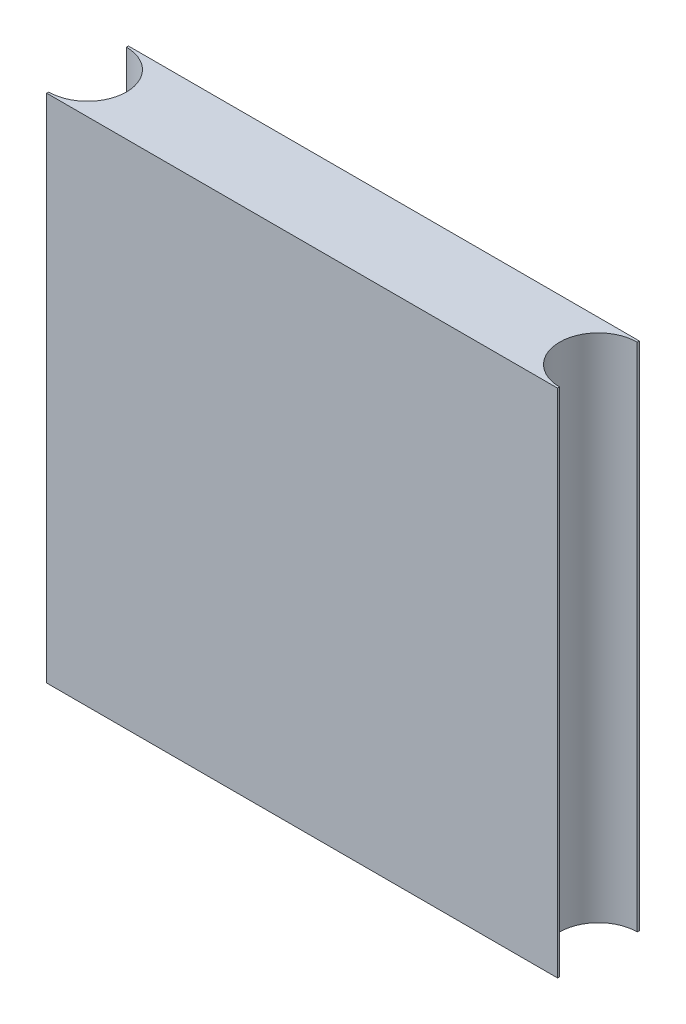
SolidWorks part; units mm, degrees
ref_plane "Front Plane" through (0, 0, 0) normal (0, 0, 1) x (1, 0, 0)
ref_plane "Top Plane" through (0, 0, 0) normal (0, 1, 0) x (1, 0, 0)
ref_plane "Right Plane" through (0, 0, 0) normal (1, 0, 0) x (0, 0, -1)
sketch "Sketch1" plane through (0, 0, 0) normal (0, 0, 1) x (1, 0, 0)
  line L1 (0, 0) -> (50, 0)
  line L2 (0, 0) -> (0, 50)
  line L3 (0, 50) -> (50, 50)
  line L4 (50, 0) -> (50, 50)
  dimension "D1" = 50
  dimension "D2" = 50
extrude "Boss-Extrude3" add sketch "Sketch1" along normal blind 8
sketch "Sketch6" plane through (0, 0, 0) normal (0, -1, 0) x (1, 0, 0)
  line L0 (0, 8) -> (0, 0) construction
  line L1 (50, 8) -> (50, 0) construction
  circle A0 centre (0, 4) radius 3.8
  circle A1 centre (50, 4) radius 3.8
  dimension "D1" = 7.6
  dimension "D2" = 7.6
extrude "Cut-Extrude2" cut sketch "Sketch6" against normal blind 68
